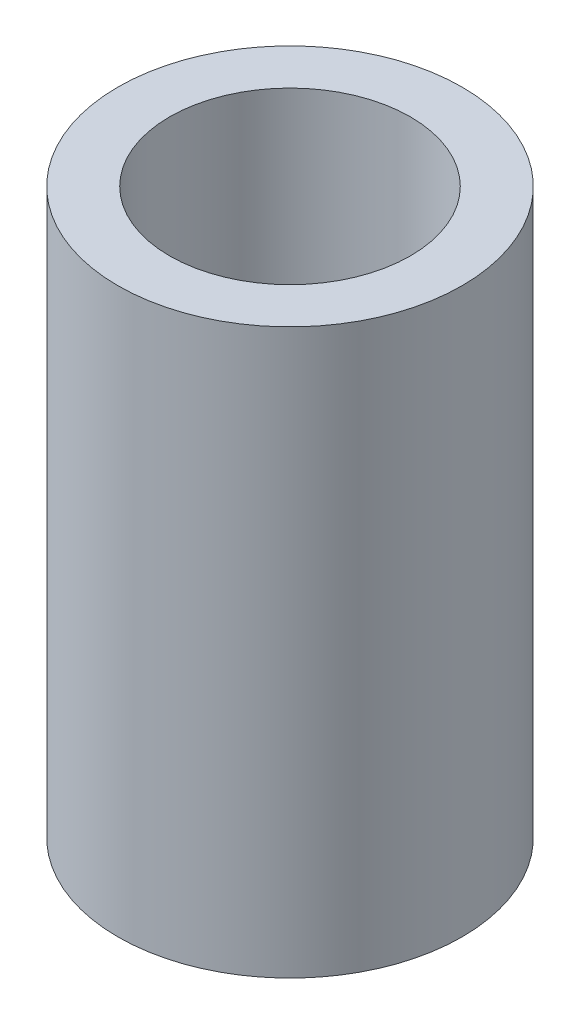
SolidWorks part; units mm, degrees
material "Custom Plastic"
ref_plane "X-Y Datum" through (0, 0, 0) normal (0, 0, 1) x (1, 0, 0)
ref_plane "X-Z Datum" through (0, 0, 0) normal (0, 1, 0) x (1, 0, 0)
ref_plane "Y-Z Datum" through (0, 0, 0) normal (1, 0, 0) x (0, 0, -1)
sketch "Sketch1" plane through (0, 0, 0) normal (0, 1, 0) x (1, 0, 0)
  circle A0 centre (0, 0) radius 2
  circle A1 centre (0, 0) radius 2.8575
  dimension "D1" = 4
  dimension "D2" = 5.715
extrude "Boss-Extrude1" add sketch "Sketch1" against normal blind 9.3662
